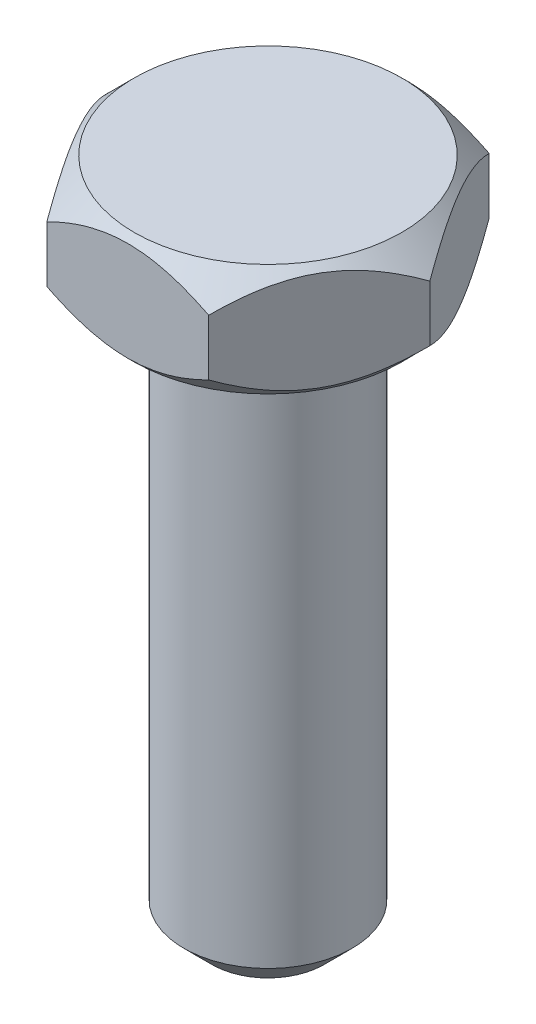
SolidWorks part; units mm, degrees
ref_plane "Спереди" through (0, 0, 0) normal (0, 0, 1) x (1, 0, 0)
ref_plane "Сверху" through (0, 0, 0) normal (0, 1, 0) x (1, 0, 0)
ref_plane "Справа" through (0, 0, 0) normal (1, 0, 0) x (0, 0, -1)
sketch "Эскиз1" plane through (0, 0, 0) normal (0, 1, 0) x (1, 0, 0)
  line L0 (-2.8868, 5) -> (2.8868, 5)
  line L1 (2.8868, 5) -> (5.7735, 0)
  line L2 (5.7735, 0) -> (2.8868, -5)
  line L3 (2.8868, -5) -> (-2.8868, -5)
  line L4 (-2.8868, -5) -> (-5.7735, 0)
  line L5 (-5.7735, 0) -> (-2.8868, 5)
  dimension "D1" = 5
  dimension "D2" = 120
  dimension "D3" = 120
  dimension "D4" = 120
  dimension "D5" = 120
  dimension "D6" = 5
  dimension "D7" = 5
  dimension "D8" = 5
  dimension "D9" = 5
  dimension "D10" = 5
extrude "Вытянуть1" add sketch "Эскиз1" against normal blind 4
sketch "Эскиз2" plane through (0, -4, 0) normal (0, -1, 0) x (1, 0, 0)
  circle A0 centre (0, 0) radius 3
  dimension "D1" = 6
extrude "Вытянуть2" add sketch "Эскиз2" along normal blind 20
chamfer "Фаска2" distance 1 angle 45 1 edges at (0, -24, -3)
ref_axis "Ось1" through (0, -4, 0) along (0, -1, 0)
ref_plane "Плоскость1" through (0, 0, 0) normal (0, 0, 1) x (1, 0, 0)
sketch "Эскиз3" plane through (0, 0, 0) normal (0, 0, 1) x (1, 0, 0)
  line L0 (-5.7735, -1) -> (-4.7735, 0)
  line L1 (-5.7735, -4) -> (-5.7735, 0) construction
  line L2 (-5.7735, 0) -> (-2.8868, 0) construction
  line L3 (-4.7735, 0) -> (-5.7735, 0)
  line L4 (-5.7735, 0) -> (-5.7735, -1)
  line L5 (-5.7735, -3) -> (-4.7735, -4)
  line L6 (-5.7735, -4) -> (-2.8868, -4) construction
  line L7 (-4.7735, -4) -> (-5.7735, -4)
  line L8 (-5.7735, -4) -> (-5.7735, -3)
  dimension "D1" = 1
  dimension "D2" = 1
  dimension "D3" = 1
  dimension "D4" = 1
revolve "Вырез-Повернуть1" cut sketch "Эскиз3" angle 360 about axis through (0, -4, 0) along (0, -1, 0)
